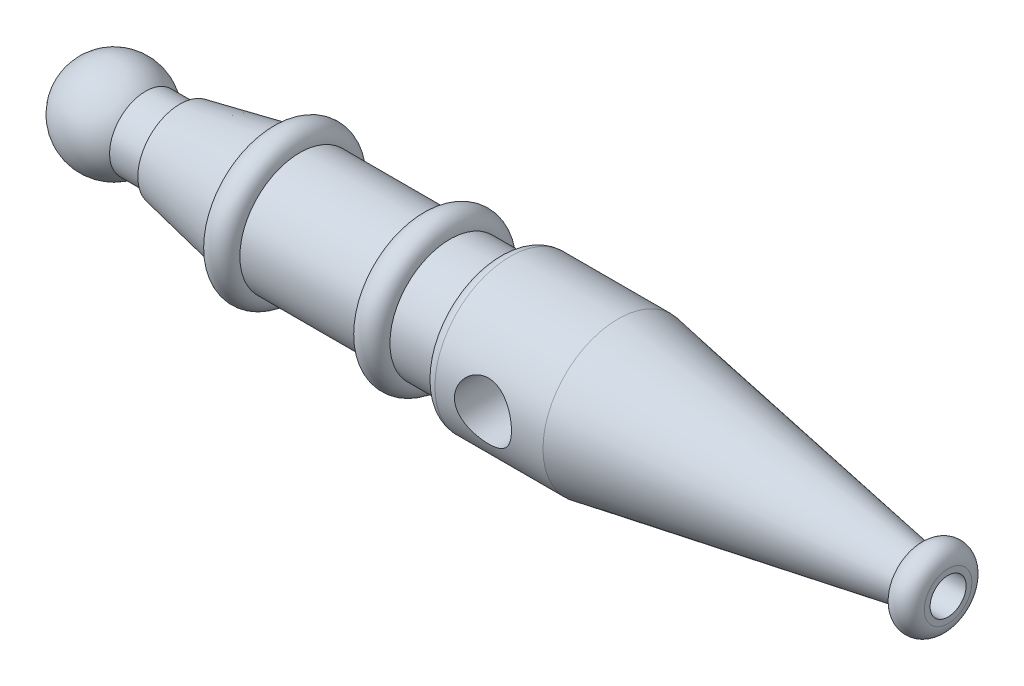
SolidWorks part; units mm, degrees
ref_plane "Front Plane" through (0, 0, 0) normal (0, 0, 1) x (1, 0, 0)
ref_plane "Top Plane" through (0, 0, 0) normal (0, 1, 0) x (1, 0, 0)
ref_plane "Right Plane" through (0, 0, 0) normal (1, 0, 0) x (0, 0, -1)
sketch "Sketch1" plane through (0, 0, 0) normal (0, 0, 1) x (1, 0, 0)
  line L0 (-66.0541, 0) -> (148.0327, 0) construction
  line L1 (-37.6004, 0) -> (-37.6004, 6)
  line L2 (-37.6004, 6) -> (-31.8919, 6)
  line L3 (-31.8919, 0) -> (-31.8919, 7)
  line L4 (8.1081, 10) -> (8.1081, 0)
  line L5 (-11.8919, 10) -> (8.1081, 10)
  line L6 (21.1081, 10) -> (21.1081, 0)
  line L7 (13.1081, 10) -> (21.1081, 10)
  line L8 (21.1081, 10) -> (21.1081, 10.5)
  line L9 (23.1081, 12.5) -> (41.1081, 12.5)
  line L10 (41.1081, 12.5) -> (91.1081, 3.9595)
  line L11 (91.1081, 3.9595) -> (91.1081, 0)
  line L12 (-31.8919, 7) -> (-16.8919, 10)
  line L13 (-16.8919, 10) -> (-16.8919, 0)
  line L14 (-11.8919, 10) -> (-11.8919, 0)
  line L15 (13.1081, 10) -> (13.1081, 0)
  line L16 (41.1081, 12.5) -> (40.9893, 0)
  line L17 (96.1081, 3.9595) -> (96.1081, 0)
  arc A0 (-37.6004, 6) -> (-50.8919, 0) centre (-42.8919, 0) ccw
  arc A1 (-11.8919, 10) -> (-16.8919, 10) centre (-14.3919, 10) ccw
  arc A2 (13.1081, 10) -> (8.1081, 10) centre (10.6081, 10) ccw
  arc A4 (96.1081, 3.9595) -> (91.1081, 3.9595) centre (93.6081, 3.9595) ccw
  arc A5 (21.1081, 10.5) -> (23.1081, 12.5) centre (23.1081, 10.5) cw
  point P32 (21.1081, 12.5)
  dimension "D2" = 5
  dimension "D10" = 2
  dimension "D1" = 7
  dimension "D3" = 15
  dimension "D4" = 28.5
  dimension "D5" = 20
  dimension "D6" = 5
  dimension "D7" = 53.5
  dimension "D8" = 12.5
  dimension "D9" = 20
  dimension "D12" = 50
  dimension "D13" = 5
revolve "Revolve1" add sketch "Sketch1" angle 360 about L0
ref_plane "Plane1" through (0, 0, 12.5) normal (0, 0, 1) x (1, 0, 0)
sketch "Sketch2" plane through (0, 0, 12.5) normal (0, 0, 1) x (1, 0, 0)
  circle A0 centre (31.1081, 0) radius 4.75
  dimension "D1" = 9.5
  dimension "D2" = 74
extrude "Cut-Extrude1" cut sketch "Sketch2" against normal blind 29 contours A0
ref_plane "Plane2" through (96.1081, 0, 0) normal (1, 0, 0) x (0, 0, -1)
sketch "Sketch5" plane through (96.1081, 0, 0) normal (1, 0, 0) x (0, 0, -1)
  circle A0 centre (0, 0) radius 3
  dimension "D1" = 6
extrude "Cut-Extrude2" cut sketch "Sketch5" against normal blind 50
